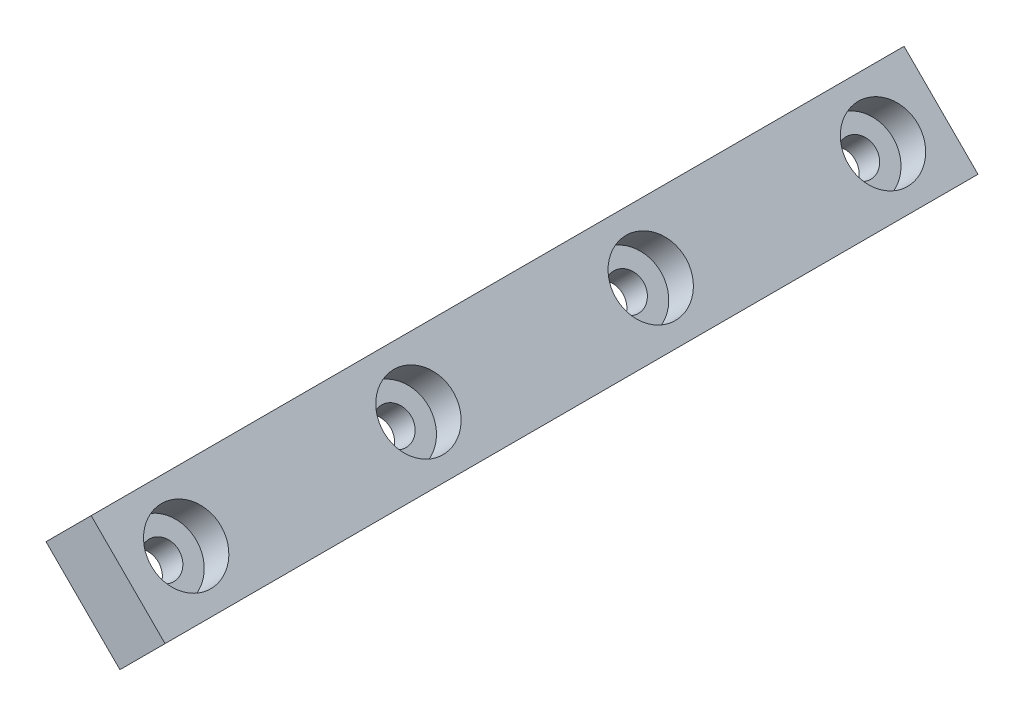
SolidWorks part; units mm, degrees
ref_plane "前视基准面" through (0, 0, 0) normal (0, 0, 1) x (1, 0, 0)
ref_plane "上视基准面" through (0, 0, 0) normal (0, 1, 0) x (1, 0, 0)
ref_plane "右视基准面" through (0, 0, 0) normal (1, 0, 0) x (0, 0, -1)
sketch "Model" plane through (0, 0, 0) normal (0, 0, 1) x (1, 0, 0)
  line L0 (0.1442, 3.5914) -> (8.1442, 3.5914) construction
  line L1 (4.1442, -0.4086) -> (4.1442, 7.5914) construction
  line L2 (22.2863, 3.5914) -> (14.2863, 3.5914) construction
  line L3 (18.2863, -0.4086) -> (18.2863, 7.5914) construction
  line L4 (-21.069, -17.6218) -> (-13.069, -17.6218) construction
  line L5 (-17.069, -21.6218) -> (-17.069, -13.6218) construction
  line L6 (43.4995, -17.6218) -> (35.4995, -17.6218) construction
  line L7 (39.4995, -21.6218) -> (39.4995, -13.6218) construction
  line L8 (-35.1609, 21.2575) -> (-26.1609, 21.2575)
  line L9 (-26.1609, 23.2575) -> (-22.3679, 23.2575)
  line L10 (-22.6609, 21.2575) -> (-16.3609, 69.2575)
  line L11 (-22.6609, 21.2575) -> (-38.6609, 21.2575)
  line L12 (-35.1609, 23.2575) -> (-38.9539, 23.2575)
  line L13 (-38.6609, 21.2575) -> (-44.9609, 69.2575)
  line L14 (-24.1609, 96.2575) -> (-16.3609, 73.2575)
  line L15 (-37.1609, 96.2575) -> (-24.1609, 96.2575)
  line L16 (-37.1609, 96.2575) -> (-44.9609, 73.2575)
  line L17 (-16.3609, 69.2575) -> (-16.3609, 73.2575)
  line L18 (-44.9609, 69.2575) -> (-44.9609, 73.2575)
  line L19 (-26.1609, 21.2575) -> (-26.1609, 23.2575)
  line L20 (-35.1609, 21.2575) -> (-35.1609, 23.2575)
  line L21 (29.9233, 62.9292) -> (29.9233, 69.9371)
  line L22 (29.9233, 62.9292) -> (29.9233, 35.9571)
  line L23 (1.3233, 62.9292) -> (1.3233, 35.9571)
  line L24 (1.3233, 69.9371) -> (29.9233, 69.9371)
  line L25 (1.3233, 62.9292) -> (1.3233, 69.9371)
  line L26 (62.8459, 91.9277) -> (70.6459, 68.9277)
  line L27 (49.8459, 91.9277) -> (42.0459, 68.9277)
  line L28 (49.8459, 91.9277) -> (62.8459, 91.9277)
  line L29 (64.3459, 16.9277) -> (70.6459, 64.9277)
  line L30 (48.3459, 16.9277) -> (42.0459, 64.9277)
  line L31 (64.3459, 16.9277) -> (48.3459, 16.9277)
  line L32 (70.6459, 64.9277) -> (70.6459, 68.9277)
  line L33 (42.0459, 64.9277) -> (42.0459, 68.9277)
  line L34 (42.0459, 68.9277) -> (70.6459, 68.9277)
  line L35 (98.2506, 52.8636) -> (103.9075, 58.5204)
  line L36 (94.3615, 56.7527) -> (98.2506, 52.8636)
  line L37 (84.1085, 67.0057) -> (89.7653, 72.6626)
  line L38 (84.1085, 67.0057) -> (87.9976, 63.1166)
  line L39 (90.4724, 65.5915) -> (96.8364, 59.2275)
  line L40 (89.7653, 72.6626) -> (103.9075, 58.5204)
  line L41 (87.6457, 43.7153) -> (91.5348, 47.6044)
  line L42 (81.2817, 50.0793) -> (87.6457, 43.7153)
  line L43 (85.1708, 53.9684) -> (91.5348, 47.6044)
  line L44 (81.2817, 50.0793) -> (85.1708, 53.9684)
  line L45 (94.3615, 56.7527) -> (96.8364, 59.2275)
  line L46 (87.9976, 63.1166) -> (90.4724, 65.5915)
  line L47 (105.6938, 43.5) -> (114.4938, 43.5)
  line L48 (114.4938, 43.5) -> (114.4938, 37)
  line L49 (103.6938, 37) -> (105.6938, 37)
  line L50 (114.4938, 37) -> (116.4938, 37)
  line L51 (116.4938, 36) -> (122.0938, 36)
  line L52 (116.4938, 37) -> (116.4938, 36)
  line L53 (103.6938, 37) -> (103.6938, 36)
  line L54 (98.0938, 36) -> (103.6938, 36)
  line L55 (85.0938, 35.5) -> (98.0938, 35.5)
  line L56 (122.0938, 36) -> (122.0938, 35.5)
  line L57 (122.0938, 35.5) -> (126.0938, 35.5)
  line L58 (105.6938, 37) -> (105.6938, 43.5)
  line L59 (98.0938, 36) -> (98.0938, 35.5)
  line L60 (85.0938, 33) -> (126.0938, 33)
  line L61 (85.0938, 35.5) -> (85.0938, 33)
  line L62 (126.0938, 35.5) -> (126.0938, 33)
  line L63 (100.4858, 19.3209) -> (103.4858, 19.3209)
  line L64 (99.4858, 18.3209) -> (100.4858, 18.3209)
  line L65 (100.4858, 19.3209) -> (100.4858, 18.3209)
  line L66 (99.4858, 22.8209) -> (99.4858, 18.3209)
  line L67 (99.4858, 23.3209) -> (103.4858, 23.3209)
  line L68 (99.4858, 23.3209) -> (99.4858, 22.8209)
  line L69 (103.4858, 23.3209) -> (103.4858, 19.3209)
  line L70 (69.3289, 25.8209) -> (110.0953, 25.8209) construction
  line L71 (51.5203, -32.4711) -> (50.1061, -33.8853)
  line L72 (14.6416, 10.0645) -> (68.4909, -43.7848)
  line L73 (65.6624, -46.6132) -> (51.5203, -32.4711)
  line L74 (65.6624, -46.6132) -> (68.4909, -43.7848)
  line L75 (50.1061, -33.8853) -> (49.035, -32.8142)
  line L76 (11.2152, -31.9355) -> (46.9137, -31.9355)
  line L77 (38.2152, -22.9772) -> (38.2152, -31.9355)
  line L78 (42.3279, -17.6218) -> (39.0939, -20.8558)
  line L79 (4.2741, 1.0645) -> (18.1564, 1.0645)
  line L80 (-25.8848, -23.9355) -> (-15.6848, -23.9355) construction
  line L81 (-20.7848, -29.0355) -> (-20.7848, -18.8355) construction
  line L82 (6.1152, 6.0645) -> (16.3152, 6.0645) construction
  line L83 (11.2152, 0.9645) -> (11.2152, 11.1645) construction
  line L84 (11.2152, -0.5802) -> (11.2152, 13.4198) construction
  line L85 (7.7888, 10.0645) -> (14.6416, 10.0645)
  line L86 (4.1442, 6.4198) -> (7.6208, 2.9431)
  line L87 (9.7421, 2.0645) -> (12.6883, 2.0645)
  line L88 (18.2863, 6.4198) -> (14.8096, 2.9431)
  line L89 (2.1528, 0.1858) -> (-12.9061, -14.8731)
  line L90 (-13.7848, -16.9944) -> (-13.7848, -25.9355)
  line L91 (36.2152, -16.9944) -> (36.2152, -25.9355)
  line L92 (53.6416, -28.9355) -> (33.2152, -28.9355) construction
  line L93 (-10.7848, -28.9355) -> (33.2152, -28.9355)
  line L94 (20.2777, 0.1858) -> (35.3366, -14.8731)
  line L95 (-19.8975, -17.6218) -> (-16.6635, -20.8558)
  line L96 (-15.7848, -22.9772) -> (-15.7848, -31.9355)
  line L97 (-24.4833, -31.9355) -> (11.2152, -31.9355)
  line L98 (3.2152, -27.0355) -> (3.2152, -31.9355)
  line L99 (19.2152, -27.0355) -> (19.2152, -31.9355)
  line L100 (19.2152, -27.0355) -> (3.2152, -27.0355)
  line L101 (7.7888, 10.0645) -> (-46.0604, -43.7848)
  line L102 (-43.232, -46.6132) -> (-46.0604, -43.7848)
  line L103 (-43.232, -46.6132) -> (-29.0899, -32.4711)
  line L104 (-29.0899, -32.4711) -> (-27.6756, -33.8853)
  line L105 (-27.6756, -33.8853) -> (-26.6046, -32.8142)
  line L106 (25.2152, -30.4355) -> (17.2152, -30.4355) construction
  line L107 (21.2152, -34.4355) -> (21.2152, -26.4355) construction
  line L108 (40.2152, -30.4355) -> (32.2152, -30.4355) construction
  line L109 (36.2152, -34.4355) -> (36.2152, -26.4355) construction
  line L110 (-2.7848, -30.4355) -> (5.2152, -30.4355) construction
  line L111 (1.2152, -34.4355) -> (1.2152, -26.4355) construction
  line L112 (-17.7848, -30.4355) -> (-9.7848, -30.4355) construction
  line L113 (-13.7848, -34.4355) -> (-13.7848, -26.4355) construction
  circle A0 centre (4.1442, 3.5914) radius 0.7835
  arc A1 (4.1442, 2.5914) -> (3.1593, 3.4177) centre (4.1442, 3.5914) ccw
  circle A2 centre (18.2863, 3.5914) radius 0.7835
  arc A3 (19.2711, 3.4177) -> (18.2863, 2.5914) centre (18.2863, 3.5914) ccw
  circle A4 centre (-17.069, -17.6218) radius 0.7835
  arc A5 (-17.069, -18.6218) -> (-18.0539, -17.7955) centre (-17.069, -17.6218) ccw
  circle A6 centre (39.4995, -17.6218) radius 0.7835
  arc A7 (40.4843, -17.7955) -> (39.4995, -18.6218) centre (39.4995, -17.6218) ccw
  arc A8 (1.3233, 35.9571) -> (29.9233, 35.9571) centre (15.6233, 41.9371) ccw
  circle A9 centre (56.3459, 36.9277) radius 6.5
  arc A10 (49.035, -32.8142) -> (46.9137, -31.9355) centre (46.9137, -34.9355) ccw
  arc A11 (39.0939, -20.8558) -> (38.2152, -22.9772) centre (41.2152, -22.9772) ccw
  arc A12 (20.2777, 0.1858) -> (18.1564, 1.0645) centre (18.1564, -1.9355) ccw
  arc A13 (4.2741, 1.0645) -> (2.1528, 0.1858) centre (4.2741, -1.9355) ccw
  circle A14 centre (-20.7848, -23.9355) radius 2.1
  circle A15 centre (43.2152, -23.9355) radius 2.1
  circle A16 centre (11.2152, 6.0645) radius 2.1
  arc A17 (7.6208, 2.9431) -> (9.7421, 2.0645) centre (9.7421, 5.0645) ccw
  arc A18 (12.6883, 2.0645) -> (14.8096, 2.9431) centre (12.6883, 5.0645) ccw
  arc A19 (-12.9061, -14.8731) -> (-13.7848, -16.9944) centre (-10.7848, -16.9944) ccw
  arc A20 (-13.7848, -25.9355) -> (-10.7848, -28.9355) centre (-10.7848, -25.9355) ccw
  arc A21 (36.2152, -16.9944) -> (35.3366, -14.8731) centre (33.2152, -16.9944) ccw
  arc A22 (33.2152, -28.9355) -> (36.2152, -25.9355) centre (33.2152, -25.9355) ccw
  arc A23 (-24.4833, -31.9355) -> (-26.6046, -32.8142) centre (-24.4833, -34.9355) ccw
  arc A24 (-15.7848, -22.9772) -> (-16.6635, -20.8558) centre (-18.7848, -22.9772) ccw
extrude "凸台-拉伸2" add sketch "Model" along normal blind 75 contours L44 L42 L41 L43
sketch "草图5" plane through (69.5696, 69.5696, 0) normal (0.7071, 0.7071, 0) x (0, 0, -1)
  line L0 (-75, -22.0634) -> (-75, -31.0634) construction
  line L1 (0, -22.0634) -> (0, -31.0634) construction
  circle A0 centre (-65, -26.5634) radius 1.5
  circle A1 centre (-45, -26.5634) radius 1.5
  circle A2 centre (-25, -26.5634) radius 1.5
  circle A3 centre (-5, -26.5634) radius 1.5
  point P10 (0, -26.5634)
  dimension "D1" = 3
  dimension "D2" = 3
  dimension "D3" = 3
  dimension "D4" = 3
  dimension "D5" = 10
  dimension "D6" = 20
  dimension "D7" = 20
  dimension "D8" = 20
  dimension "D9" = 5
extrude "切除-拉伸1" cut sketch "草图5" against normal blind 75
sketch "草图7" plane through (69.5696, 69.5696, 0) normal (0.7071, 0.7071, 0) x (0, 0, -1)
  circle A0 centre (-5, -26.5634) radius 3
  circle A1 centre (-25, -26.5634) radius 3
  circle A2 centre (-45, -26.5634) radius 3
  circle A3 centre (-65, -26.5634) radius 3
extrude "切除-拉伸2" cut sketch "草图7" against normal blind 3
sketch "草图8" plane through (0, 0, 75) normal (0, 0, 1) x (1, 0, 0)
  line L0 (87.6457, 43.7153) -> (91.5348, 47.6044)
  line L1 (87.6457, 43.7153) -> (81.2449, 50.1161)
  line L2 (91.5348, 47.6044) -> (85.134, 54.0052)
  line L3 (81.2449, 50.1161) -> (85.134, 54.0052)
extrude "切除-拉伸3" cut sketch "草图8" against normal blind 5
